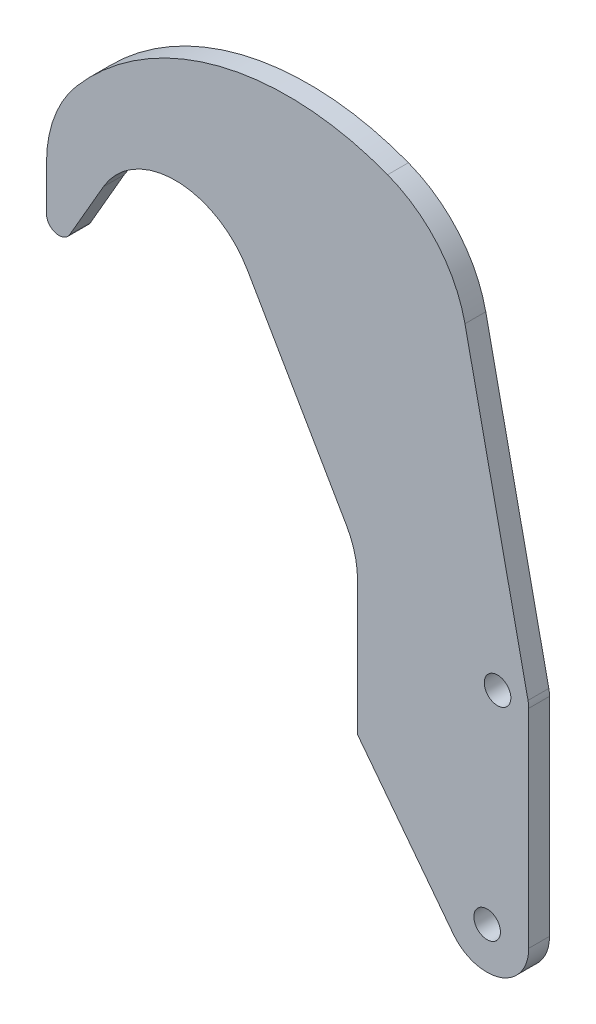
SolidWorks part; units mm, degrees
ref_plane "Front Plane" through (0, 0, 0) normal (0, 0, 1) x (1, 0, 0)
ref_plane "Top Plane" through (0, 0, 0) normal (0, 1, 0) x (1, 0, 0)
ref_plane "Right Plane" through (0, 0, 0) normal (1, 0, 0) x (0, 0, -1)
sketch "Sketch1" plane through (0, 0, 0) normal (0, 0, 1) x (1, 0, 0)
  line L0 (-10.9985, 23.8125) -> (-26.1215, -2.3812) construction
  line L1 (-15.123, -21.4313) -> (15.123, -21.4313) construction
  line L2 (26.1215, -2.3812) -> (10.9985, 23.8125) construction
  line L3 (10.9985, 23.8125) -> (26.1215, -2.3812)
  line L4 (-10.9985, 23.8125) -> (-16.1312, 14.9225)
  line L5 (-19.6859, 15.875) -> (-19.6859, 28.575)
  line L8 (53.975, -12.7) -> (53.975, -44.45)
  line L9 (47.625, -50.8) -> (47.4961, -50.8)
  line L15 (53.8696, -11.7034) -> (42.458, 41.6228)
  line L16 (27.823, -8.7312) -> (27.823, -29.2393)
  line L17 (27.823, -29.2393) -> (42.458, -48.3152)
  circle A0 centre (0, 0) radius 21.4313 construction
  arc A1 (10.9985, 23.8125) -> (-10.9985, 23.8125) centre (0, 17.4625) ccw construction
  arc A2 (-26.1215, -2.3812) -> (-15.123, -21.4313) centre (-15.123, -8.7313) ccw construction
  arc A3 (15.123, -21.4313) -> (26.1215, -2.3812) centre (15.123, -8.7312) ccw construction
  arc A4 (-10.9985, 23.8125) -> (10.9985, 23.8125) centre (0, 17.4625) cw
  arc A5 (26.1215, -2.3812) -> (27.823, -8.7312) centre (15.123, -8.7312) cw
  arc A6 (53.975, -12.7) -> (53.8696, -11.7034) centre (49.2125, -12.7) ccw
  arc A9 (-19.6859, 15.875) -> (-16.1312, 14.9225) centre (-17.7809, 15.875) ccw
  arc A10 (47.625, -50.8) -> (53.975, -44.45) centre (47.625, -44.45) ccw
  arc A11 (42.458, -48.3152) -> (47.4961, -50.8) centre (47.4961, -44.45) ccw
  circle A12 centre (47.625, -44.45) radius 2.032
  circle A15 centre (49.2125, -12.7) radius 2.032
  arc A16 (-19.6859, 28.575) -> (42.458, 41.6228) centre (17.2053, 7.3828) cw
  point P15 (42.458, 35.2728)
  dimension "D2" = 12.7
  dimension "D3" = 9.525
  dimension "D1" = 42.8625
  dimension "D4" = 30
  dimension "D5" = 1.905
  dimension "D12" = 4.064
  dimension "D9" = 50.8
  dimension "D7" = 42.545
  dimension "D6" = 12.7
  dimension "D8" = 15.875
  dimension "D14" = 47.625
  dimension "D15" = 44.45
  dimension "D16" = 31.75
extrude "Boss-Extrude1" add sketch "Sketch1" along normal mid plane 3.175
fillet "Fillet1" radius 19.05 2 edges at (-19.6859, 28.575, 0) (42.458, 41.6228, 0)
